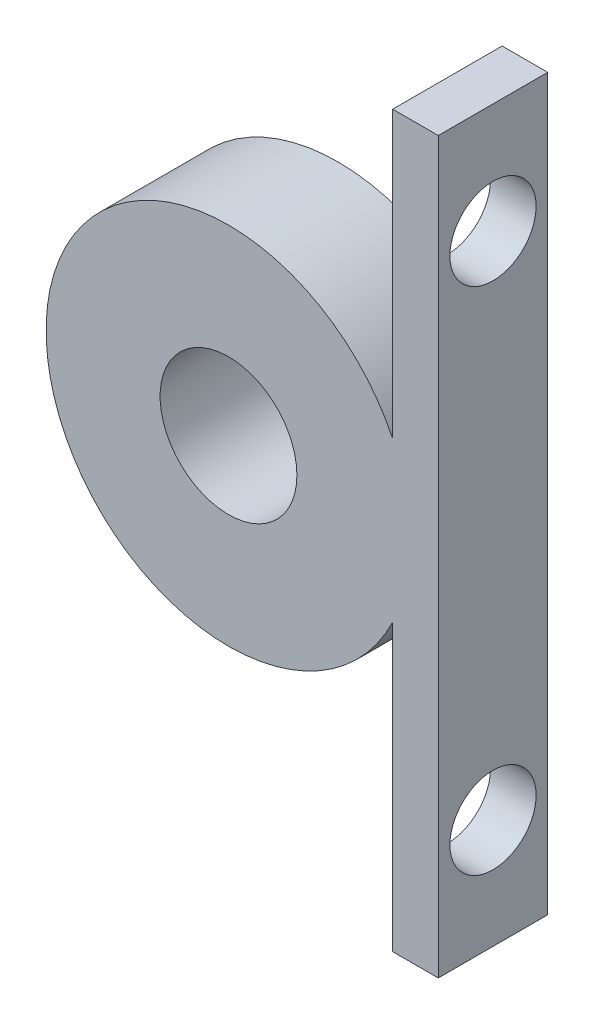
SolidWorks part; units mm, degrees
ref_plane "Front Plane" through (0, 0, 0) normal (0, 0, 1) x (1, 0, 0)
ref_plane "Top Plane" through (0, 0, 0) normal (0, 1, 0) x (1, 0, 0)
ref_plane "Right Plane" through (0, 0, 0) normal (1, 0, 0) x (0, 0, -1)
sketch "Sketch1" plane through (0, 0, 0) normal (0, 0, 1) x (1, 0, 0)
  line L0 (0, 22.784) -> (0, -28.016)
  line L1 (0, -28.016) -> (3.175, -28.016)
  line L2 (3.175, -28.016) -> (3.175, 22.784)
  line L3 (3.175, 22.784) -> (0, 22.784)
  line L4 (-11.43, -2.616) -> (3.175, -2.616) construction
  circle A0 centre (-11.43, -2.616) radius 12.7
  circle A1 centre (-11.43, -2.616) radius 4.7625
  point P9 (3.175, -2.616)
  dimension "D2" = 9.525
  dimension "D3" = 25.4
  dimension "D1" = 3.175
  dimension "D4" = 14.605
  dimension "D5" = 50.8
  dimension "D6" = 25.4
extrude "Boss-Extrude1" add sketch "Sketch1" along normal blind 7.62 contours L0 A0 A1 | A0 L0 L1 L2 L3 | L0 A0 | L4 L0 A0 | L4 A0 L0 L1 L2
ref_plane "Plane1" through (5.715, 0, 0) normal (1, 0, 0) x (0, 0, -1)
sketch "Sketch3" plane through (5.715, 0, 0) normal (1, 0, 0) x (0, 0, -1)
  line L0 (-3.81, 22.784) -> (-3.81, -28.016) construction
  line L1 (-7.62, 22.784) -> (0, 22.784) construction
  line L2 (-7.62, -28.016) -> (0, -28.016) construction
  line L3 (-3.81, -28.016) -> (-3.81, -20.396)
  line L4 (-3.81, 22.784) -> (-3.81, 15.1167)
  circle A0 centre (-3.81, 15.1167) radius 3
  circle A1 centre (-3.81, -20.396) radius 3
extrude "Cut-Extrude1" cut sketch "Sketch3" against normal blind 7.62 contours L0 L4 A0 | L4 L0 A0 | L0 A1 L3 | A1 L0 L3
